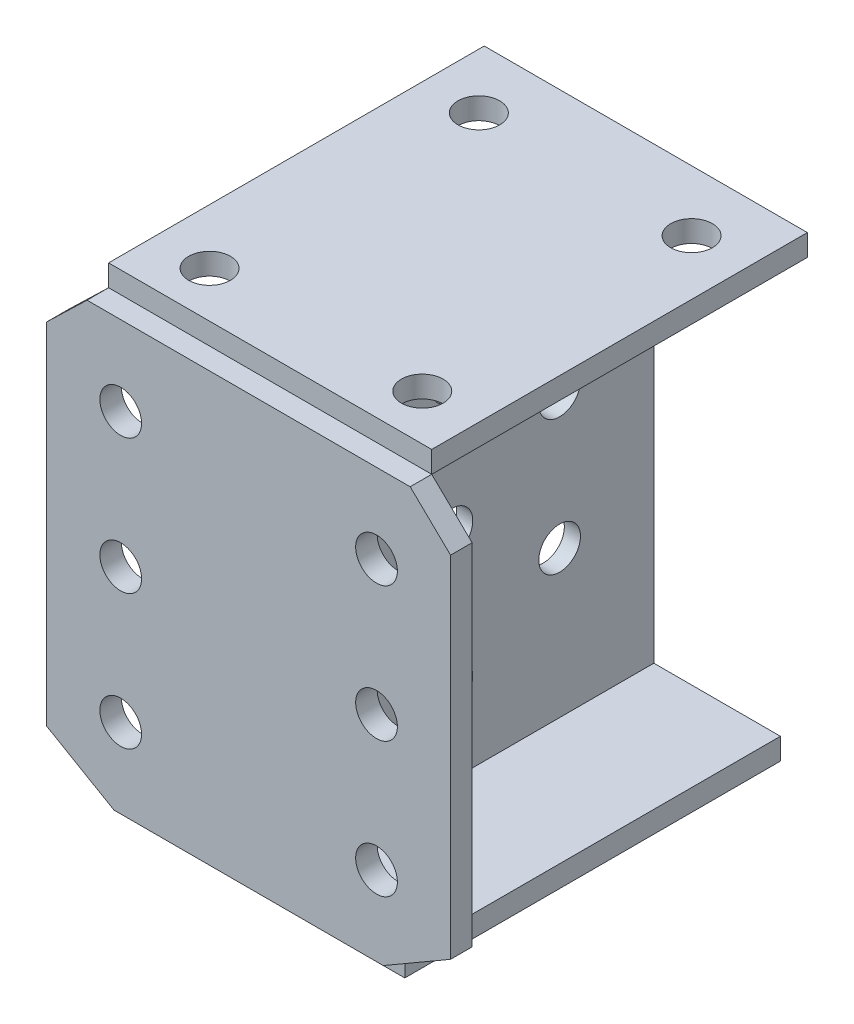
SolidWorks part; units mm, degrees
ref_plane "前视基准面" through (0, 0, 0) normal (0, 0, 1) x (1, 0, 0)
ref_plane "上视基准面" through (0, 0, 0) normal (0, 1, 0) x (1, 0, 0)
ref_plane "右视基准面" through (0, 0, 0) normal (1, 0, 0) x (0, 0, -1)
sketch "草图1" plane through (0, 0, 0) normal (0, 0, 1) x (1, 0, 0)
  line L0 (-1000, 0) -> (49000, 0) construction
  line L1 (0, -1000) -> (0, 49000) construction
  line L2 (-120, 175) -> (120, 175)
  line L3 (120, 175) -> (120, 159)
  line L4 (120, 159) -> (6, 159)
  line L5 (6, 159) -> (6, -159)
  line L6 (6, -159) -> (100, -159)
  line L7 (100, -159) -> (100, -175)
  line L8 (100, -175) -> (-100, -175)
  line L9 (-100, -175) -> (-100, -159)
  line L10 (-100, -159) -> (-6, -159)
  line L11 (-6, -159) -> (-6, 159)
  line L12 (-6, 159) -> (-120, 159)
  line L13 (-120, 159) -> (-120, 175)
  dimension "D1" = 16
  dimension "D2" = 12
  dimension "D3" = 350
  dimension "D4" = 240
  dimension "D5" = 200
  dimension "D6" = 16
extrude "拉伸1" add sketch "草图1" along normal mid plane 279
sketch "草图2" plane through (0, 0, 139.5) normal (0, 0, 1) x (1, 0, 0)
  line L0 (0, -1000) -> (0, 49000) construction
  line L1 (-150, 130) -> (-150, -130)
  line L2 (-120, 159) -> (120, 159)
  line L3 (-120, 159) -> (-150, 130)
  line L4 (-150, -130) -> (-100, -159)
  line L5 (-1000, 0) -> (49000, 0) construction
  line L6 (-100, -159) -> (100, -159)
  line L7 (150, -130) -> (100, -159)
  line L8 (150, 130) -> (150, -130)
  line L9 (120, 159) -> (150, 130)
  dimension "D1" = 45
  dimension "D2" = 45
  dimension "D3" = 260
  dimension "D4" = 150
extrude "拉伸2" add sketch "草图2" along normal blind 16 separate body
sketch "草图3" plane through (0, 0, 155.5) normal (0, 0, 1) x (1, 0, 0)
  line L0 (-1000, 0) -> (49000, 0) construction
  line L1 (0, -1000) -> (0, 49000) construction
  line L4 (120, 175) -> (-120, 175) construction
  line L5 (-100, -175) -> (100, -175) construction
  circle A0 centre (-95, 100) radius 15.5
  circle A1 centre (-95, 0) radius 15.5
  circle A2 centre (-95, -100) radius 15.5
  circle A3 centre (95, -100) radius 15.5
  circle A4 centre (95, 0) radius 15.5
  circle A5 centre (95, 100) radius 15.5
  dimension "D1" = 31
  dimension "D2" = 95
  dimension "D3" = 75
  dimension "D4" = 100
  dimension "D5" = 75
extrude "拉伸3" cut sketch "草图3" against normal through all
sketch "草图4" plane through (-6, 0, 0) normal (-1, 0, 0) x (0, 0, 1)
  line L0 (-1000, 0) -> (49000, 0) construction
  line L1 (0, -1000) -> (0, 49000) construction
  line L2 (155.5, 130) -> (155.5, -130) construction
  line L3 (139.5, 175) -> (-139.5, 175) construction
  line L4 (10.5, 100) -> (10.5, 0) construction
  line L5 (-139.5, 159) -> (-139.5, -159) construction
  circle A0 centre (10.5, 100) radius 15.5
  circle A1 centre (10.5, 0) radius 15.5
  circle A2 centre (10.5, -100) radius 15.5
  circle A3 centre (-69.5, 50) radius 15.5
  circle A4 centre (-69.5, -50) radius 15.5
  dimension "D1" = 31
  dimension "D8" = 100
  dimension "D2" = 145
  dimension "D3" = 75
  dimension "D4" = 100
  dimension "D5" = 80
  dimension "D6" = 70
  dimension "D7" = 50
extrude "拉伸4" cut sketch "草图4" against normal blind 16
sketch "草图5" plane through (0, 175, 0) normal (0, 1, 0) x (1, 0, 0)
  line L0 (-1000, 0) -> (49000, 0) construction
  line L1 (0, -1000) -> (0, 49000) construction
  line L3 (120, 139.5) -> (-120, 139.5) construction
  line L4 (120, -155.5) -> (-120, -155.5) construction
  circle A0 centre (79, -105.5) radius 15.5
  circle A1 centre (79, 94.5) radius 15.5
  circle A2 centre (-79, 94.5) radius 15.5
  circle A3 centre (-79, -105.5) radius 15.5
  dimension "D1" = 31
  dimension "D2" = 50
  dimension "D3" = 79
  dimension "D4" = 200
  dimension "D5" = 45
extrude "拉伸5" cut sketch "草图5" against normal blind 16
